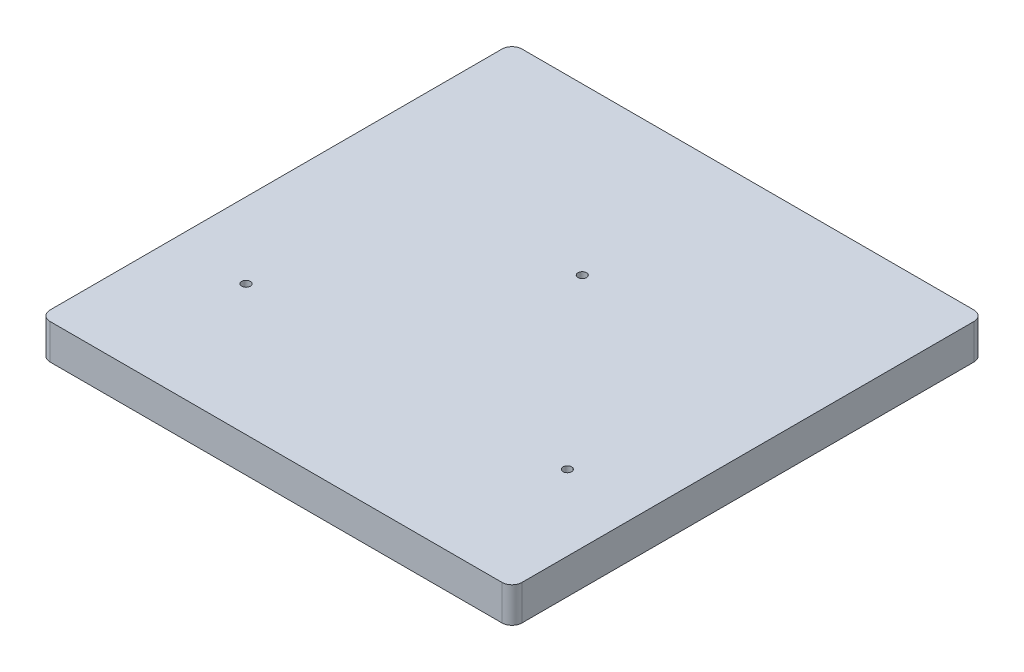
SolidWorks part; units mm, degrees
ref_plane "Front Plane" through (0, 0, 0) normal (0, 0, 1) x (1, 0, 0)
ref_plane "Top Plane" through (0, 0, 0) normal (0, 1, 0) x (1, 0, 0)
ref_plane "Right Plane" through (0, 0, 0) normal (1, 0, 0) x (0, 0, -1)
sketch "Sketch1" plane through (0, 0, 0) normal (0, 0, 1) x (1, 0, 0)
  line L7 (-76.2, -5.5563) -> (76.2, -5.5563)
  line L8 (-76.2, -5.5563) -> (-76.2, 5.5562)
  line L9 (-76.2, 5.5562) -> (76.2, 5.5562)
  line L10 (76.2, -5.5563) -> (76.2, 5.5562)
  line L11 (-76.2, -5.5563) -> (76.2, 5.5562) construction
  line L12 (-76.2, 5.5562) -> (76.2, -5.5563) construction
  point P4 (0, 0)
  point P14 (0, 0)
  dimension "Thickness" = 11.1125
  dimension "Width" = 152.4
sketch "Sketch2" plane through (0, 0, 0) normal (0, 1, 0) x (0, 0, -1)
  line L0 (76.2, 76.2) -> (-76.2, 76.2) construction
  point P4 (0, 76.2)
  dimension "Length" = 152.4
sketch "Sketch3" plane through (0, 0, 0) normal (0, 0, 1) x (1, 0, 0)
  line L6 (-76.2, 5.5562) -> (76.2, 5.5562)
  line L7 (76.2, 5.5562) -> (76.2, -5.5563)
  line L8 (76.2, -5.5563) -> (-76.2, -5.5563)
  line L9 (-76.2, -5.5563) -> (-76.2, 5.5562)
extrude "Boss-Extrude1" add sketch "Sketch3" along normal mid plane 152.4
sketch "Sketch4" plane through (0, 5.5562, 0) normal (0, 1, 0) x (1, 0, 0)
  point P0 (0, 22.2235)
  point P1 (50.8, -33.3078)
  point P3 (-50.8, -33.3078)
hole_wizard "#6-32 Tapped Hole1" positions "Sketch4" profile "Sketch5" tap size "#6-32" standard "ANSI Inch" end condition through all
sketch "Sketch5" plane through (0, 5.5562, -22.2235) normal (1, 0, 0) x (0, 0, 1)
  line L0 (0, 0) -> (0, 11.1125)
  line L1 (0, 11.1125) -> (1.3525, 11.1125)
  line L2 (1.3525, 11.1125) -> (1.3525, 0)
  line L5 (1.3525, 0) -> (0, 0)
  line L11 (0, -6.35) -> (0, 107.95) construction
  dimension "Thru Tap Drill Dia." = 2.7051
  dimension "Thru Tap Drill Depth" = 11.1125
cosmetic thread "Hole Thread1" parameters "D2"=3.5052
cosmetic thread "Hole Thread2" parameters "D2"=3.5052
cosmetic thread "Hole Thread3" parameters "D2"=3.5052
sketch "Sketch6" plane through (0, 5.5562, 0) normal (0, 1, 0) x (1, 0, 0)
  line L1 (-71.4375, -74.6125) -> (71.4375, -74.6125)
  line L2 (-74.6125, -71.4375) -> (-74.6125, 71.4375)
  line L3 (-71.4375, 74.6125) -> (71.4375, 74.6125)
  line L4 (61.9125, 74.6125) -> (-61.9125, 74.6125)
  line L5 (-74.6125, 61.9125) -> (-74.6125, -61.9125)
  line L6 (-61.9125, -74.6125) -> (61.9125, -74.6125)
  line L7 (74.6125, -61.9125) -> (74.6125, 61.9125)
  line L8 (61.9125, 74.6125) -> (-61.9125, 74.6125) construction
  line L9 (-74.6125, 61.9125) -> (-74.6125, -61.9125) construction
  line L10 (-61.9125, -74.6125) -> (61.9125, -74.6125) construction
  line L11 (74.6125, -61.9125) -> (74.6125, 61.9125) construction
  line L12 (74.6125, -71.4375) -> (74.6125, 71.4375)
  line L13 (-74.6125, -74.6125) -> (74.6125, 74.6125) construction
  line L14 (-74.6125, 74.6125) -> (74.6125, -74.6125) construction
  arc A0 (-71.4375, -74.6125) -> (-74.6125, -71.4375) centre (-71.4375, -71.4375) cw
  arc A1 (71.4375, -74.6125) -> (74.6125, -71.4375) centre (71.4375, -71.4375) ccw
  arc A2 (71.4375, 74.6125) -> (74.6125, 71.4375) centre (71.4375, 71.4375) cw
  arc A3 (-74.6125, 71.4375) -> (-71.4375, 74.6125) centre (-71.4375, 71.4375) cw
  arc A4 (-61.9125, 74.6125) -> (-74.6125, 61.9125) centre (-61.9125, 61.9125) ccw
  arc A5 (-74.6125, -61.9125) -> (-61.9125, -74.6125) centre (-61.9125, -61.9125) ccw
  arc A6 (61.9125, -74.6125) -> (74.6125, -61.9125) centre (61.9125, -61.9125) ccw
  arc A7 (74.6125, 61.9125) -> (61.9125, 74.6125) centre (61.9125, 61.9125) ccw
  arc A8 (-61.9125, 74.6125) -> (-74.6125, 61.9125) centre (-61.9125, 61.9125) ccw construction
  arc A9 (-74.6125, -61.9125) -> (-61.9125, -74.6125) centre (-61.9125, -61.9125) ccw construction
  arc A10 (61.9125, -74.6125) -> (74.6125, -61.9125) centre (61.9125, -61.9125) ccw construction
  arc A11 (74.6125, 61.9125) -> (61.9125, 74.6125) centre (61.9125, 61.9125) ccw construction
  point P2 (0, 0)
  dimension "D2" = 3.175
  dimension "D1" = 0
extrude "Cut-Extrude1" cut sketch "Sketch6" against normal through all flip side to cut
equation "\"D1@Boss-Extrude1\" = \"Length@Sketch2\""
